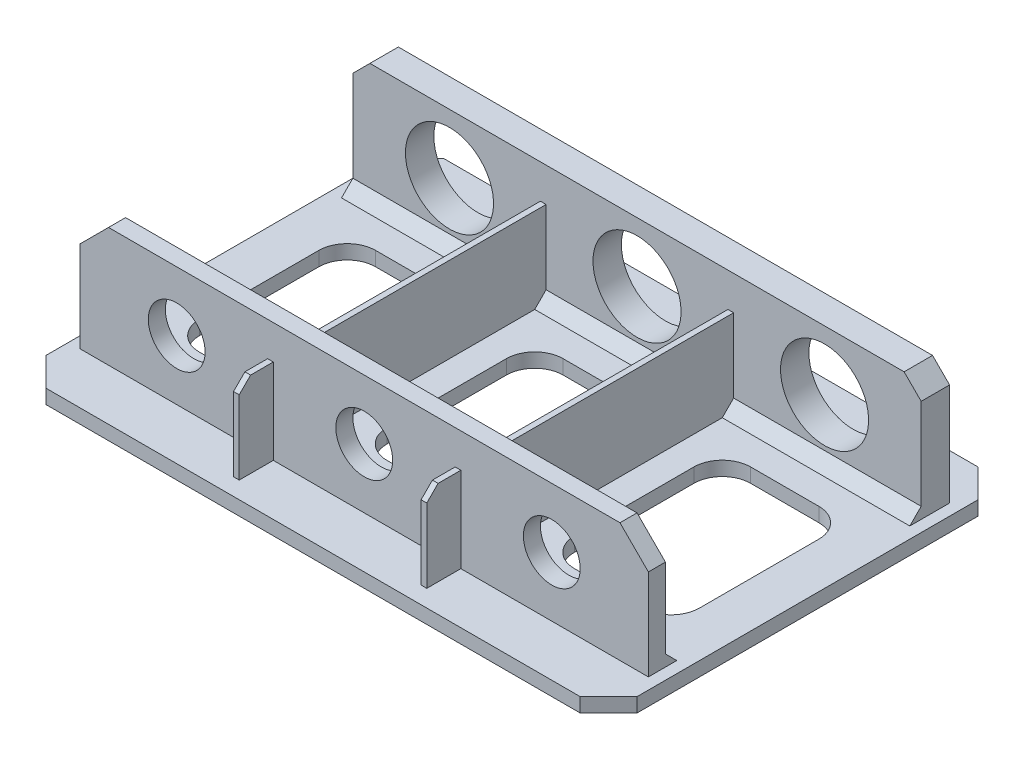
SolidWorks part; units mm, degrees
ref_plane "Front Plane" through (0, 0, 0) normal (0, 0, 1) x (1, 0, 0)
ref_plane "Top Plane" through (0, 0, 0) normal (0, 1, 0) x (1, 0, 0)
ref_plane "Right Plane" through (0, 0, 0) normal (1, 0, 0) x (0, 0, -1)
sketch "Sketch1" plane through (0, 0, 0) normal (0, 1, 0) x (1, 0, 0)
  line L1 (-50, -35) -> (50, -35)
  line L2 (-50, -35) -> (-50, 35)
  line L3 (-50, 35) -> (50, 35)
  line L4 (50, -35) -> (50, 35)
  line L5 (-50, -35) -> (50, 35) construction
  line L6 (-50, 35) -> (50, -35) construction
  point P0 (0, 0)
  dimension "D1" = 100
  dimension "D2" = 70
extrude "Boss-Extrude1" add sketch "Sketch1" along normal blind 2.5
sketch "Sketch2" plane through (0, 2.5, 0) normal (0, 1, 0) x (1, 0, 0)
  line L0 (-50, 35) -> (-50, -35) construction
  line L1 (-50, 27) -> (50, 27)
  line L2 (-50, 27) -> (-50, 22)
  line L3 (-50, 22) -> (50, 22)
  line L4 (50, 27) -> (50, 22)
  line L5 (50, -35) -> (50, 35) construction
  line L6 (50, 35) -> (-50, 35) construction
  line L8 (-50, -26) -> (50, -26)
  line L9 (-50, -26) -> (-50, -23)
  line L10 (-50, -23) -> (50, -23)
  line L11 (50, -26) -> (50, -23)
  dimension "D1" = 5
  dimension "D2" = 8
  dimension "D3" = 3
  dimension "D4" = 45
extrude "Boss-Extrude2" add sketch "Sketch2" along normal blind 21
sketch "Sketch3" plane through (0, 0, -27) normal (0, 0, -1) x (-1, 0, 0)
  line L0 (50, 23.5) -> (50, 2.5) construction
  circle A0 centre (-33, 13) radius 7.75
  circle A1 centre (0, 13) radius 7.75
  circle A2 centre (33, 13) radius 7.75
  dimension "D1" = 15.5
  dimension "D2" = 15.5
  dimension "D3" = 15.5
  dimension "D4" = 33
  dimension "D5" = 33
  dimension "D6" = 17
extrude "Cut-Extrude1" cut sketch "Sketch3" against normal blind 61
sketch "Sketch4" plane through (0, 0, 26) normal (0, 0, 1) x (1, 0, 0)
  circle A0 centre (-33, 13) radius 5
  circle A1 centre (-33, 13) radius 7.75
  circle A2 centre (0, 13) radius 7.75
  circle A3 centre (0, 13) radius 5
  circle A4 centre (33, 13) radius 7.75
  circle A5 centre (33, 13) radius 5
  dimension "D1" = 10
  dimension "D2" = 10
  dimension "D3" = 10
extrude "Boss-Extrude3" add sketch "Sketch4" against normal blind 3
sketch "Sketch5" plane through (-50, 0, 0) normal (-1, 0, 0) x (0, 0, 1)
  line L1 (-35, 2.5) -> (35, 2.5)
  line L2 (-35, 2.5) -> (-35, 0)
  line L3 (-35, 0) -> (35, 0)
  line L4 (35, 2.5) -> (35, 0)
extrude "Boss-Extrude4" add sketch "Sketch5" along normal blind 2
sketch "Sketch6" plane through (50, 0, 0) normal (1, 0, 0) x (0, 0, -1)
  line L1 (35, 0) -> (-35, 0)
  line L2 (35, 0) -> (35, 2.5)
  line L3 (35, 2.5) -> (-35, 2.5)
  line L4 (-35, 0) -> (-35, 2.5)
extrude "Boss-Extrude5" add sketch "Sketch6" along normal blind 2
chamfer "Chamfer1" distance 5 angle 45 6 edges at (-50, 23.5, 24.5) (50, 23.5, 24.5) (-52, 1.25, 35) (52, 1.25, 35) (52, 1.25, -35) (-52, 1.25, -35)
sketch "Sketch9" plane through (0, 2.5, 0) normal (0, 1, 0) x (1, 0, 0)
  line L0 (-52, -30) -> (-52, 30) construction
  line L1 (-17, 32) -> (-16, 32)
  line L2 (-17, 32) -> (-17, -32)
  line L3 (-17, -32) -> (-16, -32)
  line L4 (-16, 32) -> (-16, -32)
  line L5 (16, 32) -> (17, 32)
  line L6 (16, 32) -> (16, -32)
  line L7 (16, -32) -> (17, -32)
  line L8 (17, 32) -> (17, -32)
  line L9 (52, 30) -> (52, -30) construction
  line L10 (47, 35) -> (-47, 35) construction
  line L11 (-47, -35) -> (47, -35) construction
  dimension "D1" = 1
  dimension "D2" = 35
  dimension "D3" = 1
  dimension "D4" = 35
  dimension "D5" = 3
  dimension "D6" = 3
  dimension "D7" = 3
  dimension "D8" = 3
extrude "Boss-Extrude8" add sketch "Sketch9" along normal blind 15
chamfer "Chamfer3" distance 2 angle 45 4 edges at (16.5, 17.5, 32) (-16.5, 17.5, 32) (-16.5, 17.5, -32) (16.5, 17.5, -32)
chamfer "Chamfer4" distance 3 angle 45 2 edges at (50, 23.5, -24.5) (-50, 23.5, -24.5)
chamfer "Chamfer5" distance 2 angle 45 4 edges at (33.5, 2.5, 23) (-33.5, 2.5, 23) (33.5, 2.5, -22) (-33.5, 2.5, -22)
sketch "Sketch11" plane through (0, 2.5, 0) normal (0, 1, 0) x (1, 0, 0)
  line L0 (16, 20) -> (-16, 20) construction
  line L1 (-11, 15) -> (11, 15)
  line L2 (-11, 15) -> (-11, -16)
  line L3 (-11, -16) -> (11, -16)
  line L4 (11, 15) -> (11, -16)
  line L5 (-16, -21) -> (16, -21) construction
  line L6 (16, 20) -> (16, -21) construction
  line L7 (-16, -21) -> (-16, 20) construction
  line L8 (-17, 20) -> (-50, 20) construction
  line L9 (-22, 15) -> (-44, 15)
  line L10 (-22, 15) -> (-22, -16)
  line L11 (-22, -16) -> (-44, -16)
  line L12 (-44, 15) -> (-44, -16)
  line L13 (22, 15) -> (44, 15)
  line L14 (22, 15) -> (22, -16)
  line L15 (22, -16) -> (44, -16)
  line L16 (44, 15) -> (44, -16)
  line L17 (-50, -21) -> (-17, -21) construction
  line L18 (-17, 20) -> (-17, -21) construction
  line L19 (-52, -30) -> (-52, 30) construction
  line L20 (17, -21) -> (17, 20) construction
  line L21 (52, 30) -> (52, -30) construction
  point P30 (44, -0.5)
  dimension "D1" = 5
  dimension "D2" = 5
  dimension "D3" = 5
  dimension "D4" = 5
  dimension "D5" = 5
  dimension "D6" = 5
  dimension "D7" = 5
  dimension "D8" = 8
  dimension "D9" = 5
  dimension "D10" = 8
extrude "Cut-Extrude2" cut sketch "Sketch11" against normal blind 10
fillet "Fillet1" radius 5 12 edges at (44, 1.25, 16) (22, 1.25, 16) (11, 1.25, 16) (-11, 1.25, 16) (-22, 1.25, 16) (-44, 1.25, 16) (44, 1.25, -15) (22, 1.25, -15) (11, 1.25, -15) (-11, 1.25, -15) (-44, 1.25, -15) (-22, 1.25, -15)
